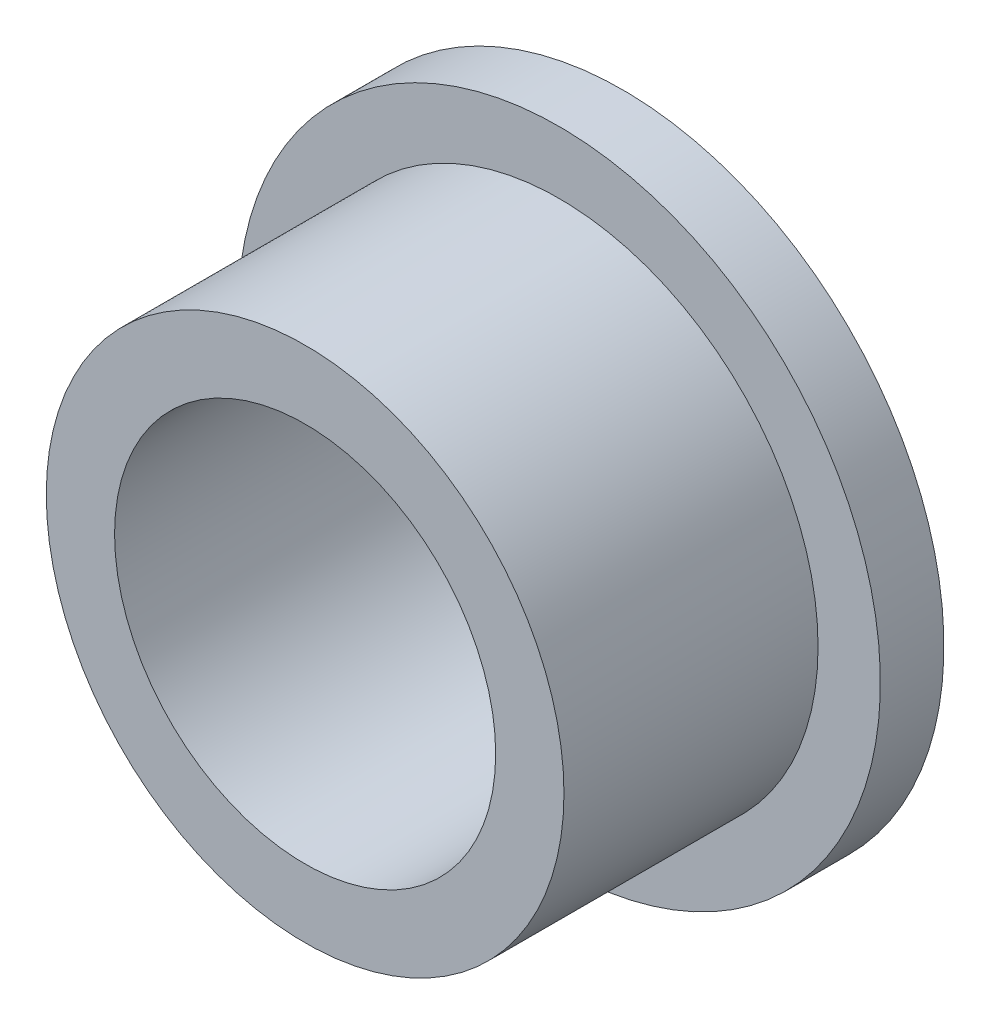
SolidWorks part; units mm, degrees
ref_plane "前视基准面" through (0, 0, 0) normal (0, 0, 1) x (1, 0, 0)
ref_plane "上视基准面" through (0, 0, 0) normal (0, 1, 0) x (1, 0, 0)
ref_plane "右视基准面" through (0, 0, 0) normal (1, 0, 0) x (0, 0, -1)
other "Configuration Table"
sketch "草图1" plane through (0, 0, 0) normal (0, 0, 1) x (1, 0, 0)
  circle A0 centre (0, 0) radius 4.075
  circle A1 centre (0, 0) radius 3
  point P5 (-0.6376, 0)
extrude "凸台-拉伸4" add sketch "草图1" along normal blind 5
sketch "草图7" plane through (0, 0, 0) normal (0, 0, -1) x (-1, 0, 0)
  circle A0 centre (0, 0) radius 5.0562
  circle A1 centre (0, 0) radius 4.075
extrude "凸台-拉伸5" add sketch "草图7" against normal blind 1
